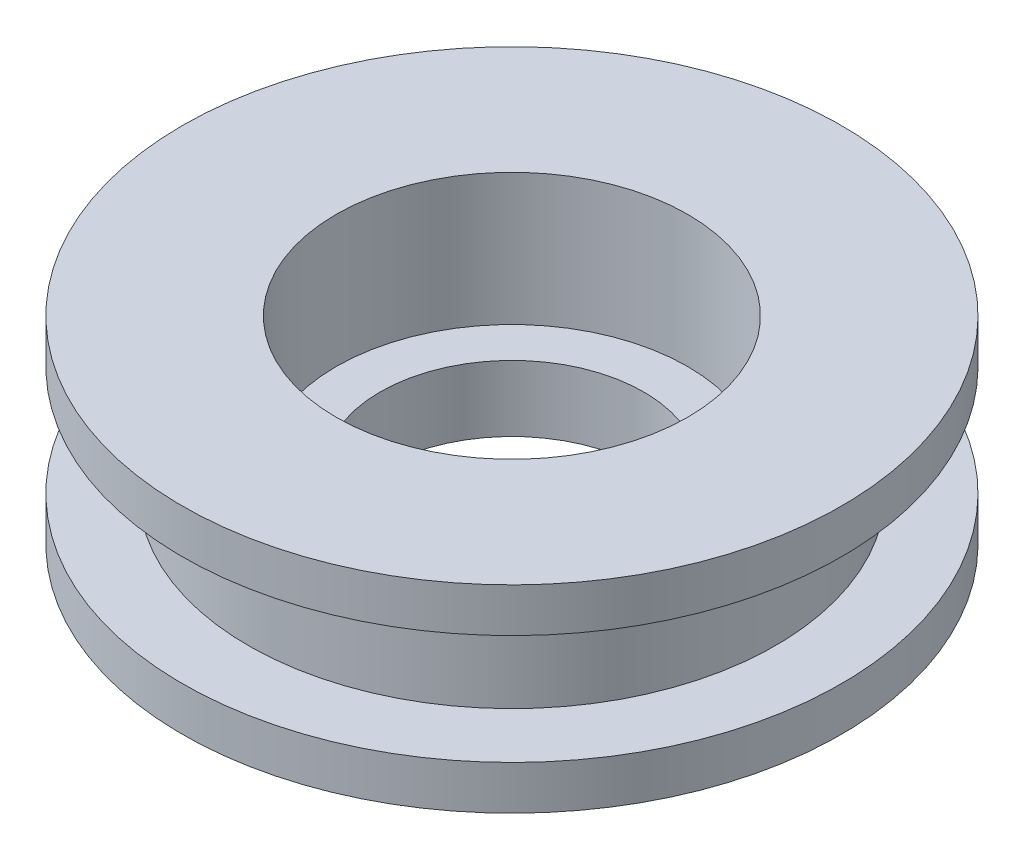
SolidWorks part; units mm, degrees
ref_plane "Plan de face" through (0, 0, 0) normal (0, 0, 1) x (1, 0, 0)
ref_plane "Plan de dessus" through (0, 0, 0) normal (0, 1, 0) x (1, 0, 0)
ref_plane "Plan de droite" through (0, 0, 0) normal (1, 0, 0) x (0, 0, -1)
sketch "Sketch1" plane through (0, 0, 0) normal (0, 0, 1) x (1, 0, 0)
  line L0 (0, 6.6206) -> (0, -3.6319) construction
  line L8 (4, 2.25) -> (4, -0.75)
  line L9 (4, 2.25) -> (7.5, 2.25)
  line L10 (7.5, 2.25) -> (7.5, 1.25)
  line L11 (7.5, 1.25) -> (6, 1.25)
  line L12 (6, 1.25) -> (6, -1.25)
  line L13 (6, -1.25) -> (7.5, -1.25)
  line L14 (7.5, -1.25) -> (7.5, -2.25)
  line L15 (7.5, -2.25) -> (3, -2.25)
  line L17 (3, -2.25) -> (3, -0.75)
  line L18 (3, -0.75) -> (4, -0.75)
  point P4 (6, 0)
  dimension "D2" = 2
  dimension "D3" = 1.5
  dimension "D5" = 2.5
  dimension "D1" = 4
  dimension "D4" = 3
  dimension "D6" = 3
  dimension "D7" = 1
revolve "Revolve1" add sketch "Sketch1" angle 360 about L0
